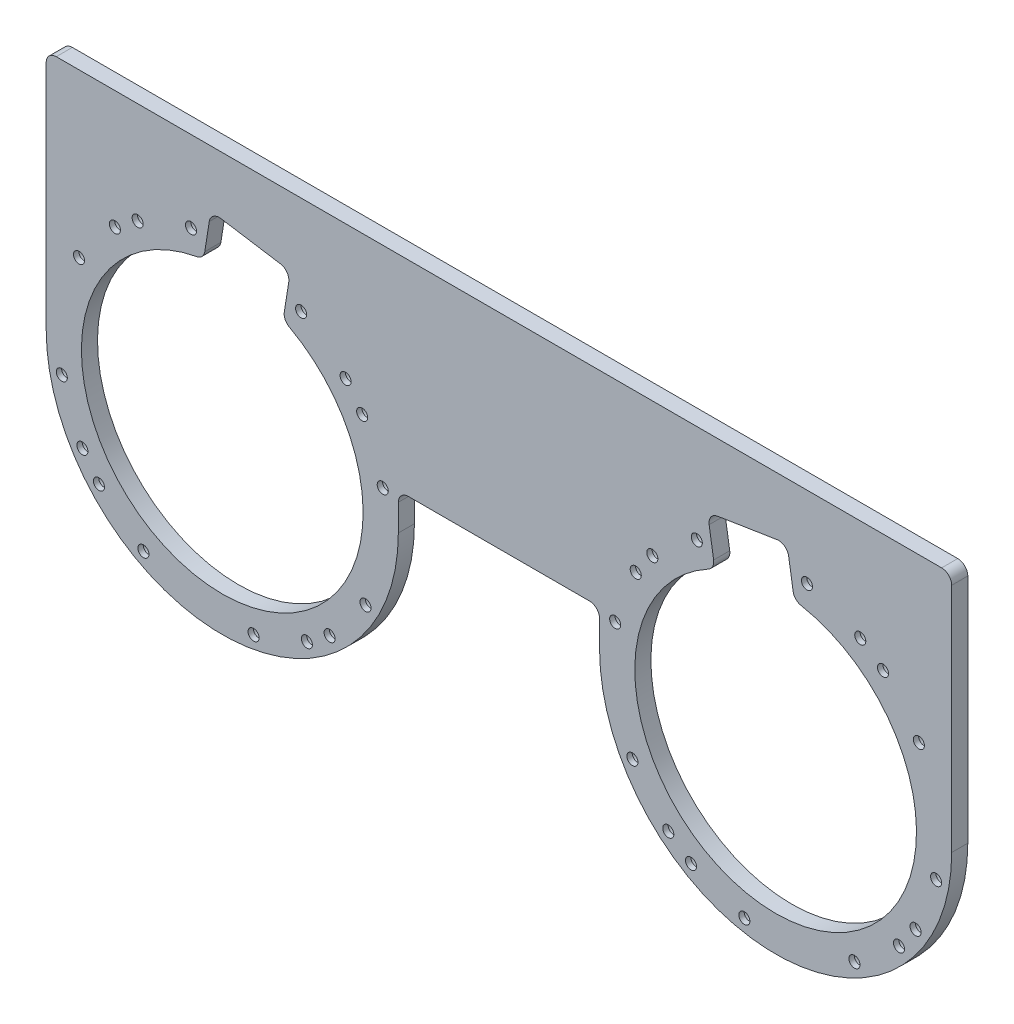
SolidWorks part; units mm, degrees
ref_plane "前视基准面" through (0, 0, 0) normal (0, 0, 1) x (1, 0, 0)
ref_plane "上视基准面" through (0, 0, 0) normal (0, 1, 0) x (1, 0, 0)
ref_plane "右视基准面" through (0, 0, 0) normal (1, 0, 0) x (0, 0, -1)
sketch "草图1" plane through (0, 0, 0) normal (0, 0, 1) x (1, 0, 0)
  circle A0 centre (0, 0) radius 70
  circle A1 centre (0, 0) radius 87.5
  dimension "D1" = 140
  dimension "D2" = 175
extrude "凸台-拉伸1" add sketch "草图1" along normal blind 8
sketch "草图2" plane through (0, 0, 8) normal (0, 0, 1) x (1, 0, 0)
  circle A0 centre (0, 0) radius 81.25 construction
  circle A2 centre (42.0516, 69.5214) radius 2.75
  circle A3 centre (53.352, 61.2791) radius 2.75
  circle A4 centre (71.1784, 39.1816) radius 2.75
  circle A6 centre (15.5646, 79.7452) radius 2.75
  dimension "D1" = 162.5
  dimension "D2" = 5.5
extrude "切除-拉伸1" cut sketch "草图2" against normal blind 10
pattern_circular "阵列(圆周)1" count 4 over 360 about axis through (0, 0, 0) along (0, 0, 1) of "切除-拉伸1"
sketch "草图3" plane through (0, 0, 8) normal (0, 0, 1) x (1, 0, 0)
  line L0 (0, 0) -> (-71.1784, -39.1816) construction
  line L1 (0, 0) -> (-89.3496, 25.8001) construction
  line L2 (0, 0) -> (-129.4054, -20.2497) construction
  line L3 (0, 0) -> (-19.2768, 123.1882) construction
  line L4 (0, 0) -> (-104.6553, 76.3337) construction
  line L5 (-42.2787, 76.6078) -> (-48.3186, 87.5518)
  line L6 (-85.8612, 16.8552) -> (-98.1271, 19.2631)
  arc A0 (-42.2787, 76.6078) -> (-85.8612, 16.8552) centre (0, 0) ccw
  arc A1 (-48.3186, 87.5518) -> (-98.1271, 19.2631) centre (0, 0) ccw
  circle A2 centre (0, 0) radius 93 construction
  circle A3 centre (-89.3496, 25.8001) radius 2.75
  circle A4 centre (-51.8618, 77.1969) radius 2.75
  circle A5 centre (-75.137, 54.8036) radius 2.75
  circle A6 centre (0, 0) radius 87.5 construction
  dimension "D4" = 100
  dimension "D5" = 186
  dimension "D6" = 5.5
  dimension "D1" = 45
  dimension "D2" = 25
  dimension "D3" = 25
  dimension "D7" = 20
extrude "凸台-拉伸2" [suppressed] add sketch "草图3" against normal up to surface (8 mm away)
pattern_circular "阵列(圆周)2" [suppressed] count 4 over 360
sketch "草图4" plane through (0, 0, 8) normal (0, 0, 1) x (1, 0, 0)
  line L0 (87.5, 120) -> (87.5, 0)
  line L3 (-87.5, 0) -> (-87.5, 120)
  line L4 (-87.5, 120) -> (87.5, 120)
  arc A0 (87.5, 0) -> (-87.5, 0) centre (0, 0) ccw
  circle A1 centre (0, 0) radius 87.5 construction
  dimension "D3" = 120
extrude "凸台-拉伸3" add sketch "草图4" against normal up to surface (8 mm away) up to face at (-76.9952, 15.5646, 0)
hole_wizard "大小mm 暗销孔1" positions "3D草图1" profile "草图5" hole size "Ø10.0" standard "GB"
sketch3d "3D草图1"
  line L0 (71.1784, 39.1816, 0) -> (71.1784, 39.1816, 8) construction
  line L1 (53.352, 61.2791, 0) -> (53.352, 61.2791, 8) construction
  line L2 (42.0516, 69.5214, 0) -> (42.0516, 69.5214, 8) construction
  line L3 (15.5646, 79.7452, 0) -> (15.5646, 79.7452, 8) construction
  line L4 (-39.1816, 71.1784, 0) -> (-39.1816, 71.1784, 8) construction
  line L5 (-61.2791, 53.352, 0) -> (-61.2791, 53.352, 8) construction
  line L6 (-69.5214, 42.0516, 0) -> (-69.5214, 42.0516, 8) construction
  line L7 (-79.7452, 15.5646, 0) -> (-79.7452, 15.5646, 8) construction
  line L8 (-71.1784, -39.1816, 0) -> (-71.1784, -39.1816, 8) construction
  line L9 (-53.352, -61.2791, 0) -> (-53.352, -61.2791, 8) construction
  line L10 (-42.0516, -69.5214, 0) -> (-42.0516, -69.5214, 8) construction
  line L11 (-15.5646, -79.7452, 0) -> (-15.5646, -79.7452, 8) construction
  line L12 (39.1816, -71.1784, 0) -> (39.1816, -71.1784, 8) construction
  line L13 (61.2791, -53.352, 0) -> (61.2791, -53.352, 8) construction
  line L14 (69.5214, -42.0516, 0) -> (69.5214, -42.0516, 8) construction
  line L15 (79.7452, -15.5646, 0) -> (79.7452, -15.5646, 8) construction
  point P0 (71.1784, 39.1816, 0)
  point P4 (53.352, 61.2791, 0)
  point P8 (42.0516, 69.5214, 0)
  point P12 (15.5646, 79.7452, 0)
  point P16 (-39.1816, 71.1784, 0)
  point P20 (-61.2791, 53.352, 0)
  point P24 (-69.5214, 42.0516, 0)
  point P28 (-79.7452, 15.5646, 0)
  point P32 (-71.1784, -39.1816, 0)
  point P36 (-53.352, -61.2791, 0)
  point P40 (-42.0516, -69.5214, 0)
  point P44 (-15.5646, -79.7452, 0)
  point P48 (39.1816, -71.1784, 0)
  point P52 (61.2791, -53.352, 0)
  point P56 (69.5214, -42.0516, 0)
  point P60 (79.7452, -15.5646, 0)
sketch "草图5" plane through (71.1784, 39.1816, 0) normal (1, 0, 0) x (0, 1, 0)
  line L0 (0, 0) -> (0, 7.0043)
  line L1 (0, 7.0043) -> (5, 4)
  line L2 (5, 4) -> (5, 0)
  line L5 (5, 0) -> (0, 0)
  line L10 (0, 7.0043) -> (-5, 4) construction
  line L11 (0, -6.35) -> (0, 107.95) construction
  dimension "孔直径" = 10
  dimension "孔深度" = 4
  dimension "导头角度" = 118
sketch "草图6" plane through (0, 0, 8) normal (0, 0, 1) x (1, 0, 0)
  line L0 (87.5, 0) -> (87.5, 120) construction
  line L1 (-87.5, 120) -> (-137.5, 120)
  line L2 (-87.5, 120) -> (-87.5, 18.2236)
  line L3 (-87.5, 18.2236) -> (-137.5, 18.2236)
  line L4 (-137.5, 120) -> (-137.5, 18.2236)
  dimension "D1" = 225
extrude "凸台-拉伸4" add sketch "草图6" against normal up to surface (8 mm away) up to face at (48.352, 61.2791, 0)
sketch "草图7" plane through (0, 0, 0) normal (0, 0, -1) x (-1, 0, 0)
  line L0 (0, 0) -> (17.2814, 109.1107) construction
  line L1 (-87.5, 120) -> (-87.5, 0) construction
  line L2 (-10.4308, 61.9913) -> (-5.6747, 92.0206)
  line L3 (-10.4308, 61.9913) -> (29.0767, 55.7339)
  line L4 (-5.6747, 92.0206) -> (33.8329, 85.7633)
  line L5 (29.0767, 55.7339) -> (33.8329, 85.7633)
  dimension "D1" = 9
  dimension "D2" = 40
  dimension "D3" = 90
extrude "切除-拉伸2" cut sketch "草图7" against normal blind 10
fillet "圆角1" radius 5 6 edges at (87.5, 120, 4) (-87.5, 18.2236, 4) (5.6747, 92.0206, 4) (-33.8329, 85.7633, 4) (-30.2477, 63.1275, 4) (9.2598, 69.3848, 4)
mirror "镜向10" about plane through (-137.5, 120, -113.395) normal (-1, 0, 0) of bodies 111 108
